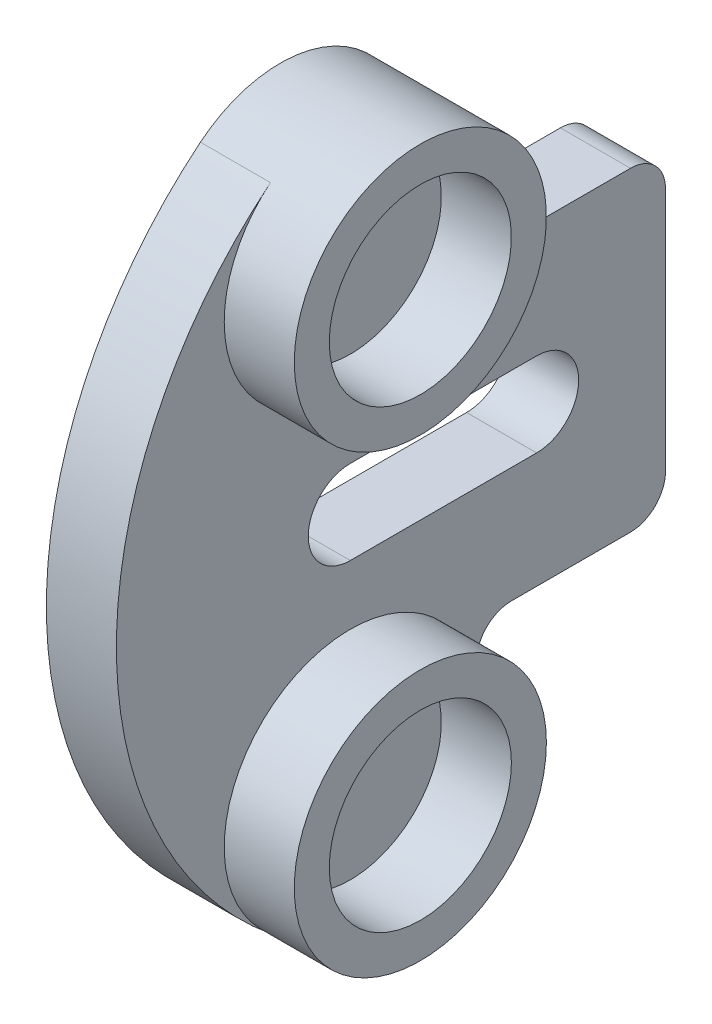
SolidWorks part; units mm, degrees
ref_plane "Front Plane" through (0, 0, 0) normal (1, 0, 0) x (0, 1, 0)
ref_plane "Top Plane" through (0, 0, 0) normal (0, 0, 1) x (0, 1, 0)
ref_plane "Right Plane" through (0, 0, 0) normal (0, 1, 0) x (-1, 0, 0)
sketch "Sketch2" plane through (0, 0, 0) normal (1, 0, 0) x (0, 1, 0)
  line L0 (6, 26.6036) -> (6, 0)
  line L1 (32.5, 8.6036) -> (27.5, 8.6036)
  line L2 (22.5, 3.6036) -> (22.5, -13.3964)
  line L3 (17.5, -18.3964) -> (-17.5, -18.3964)
  line L4 (-22.5, -13.3964) -> (-22.5, 3.6036)
  line L5 (-27.5, 8.6036) -> (-32.5, 8.6036)
  line L6 (-6, 26.6036) -> (-6, 0)
  arc A0 (-46.4286, 38.0051) -> (46.4286, 38.0051) centre (0, 0) cw
  arc A1 (32.5, 8.6036) -> (46.4286, 38.0051) centre (32.5, 26.6036) ccw
  arc A2 (-32.5, 8.6036) -> (-46.4286, 38.0051) centre (-32.5, 26.6036) cw
  arc A4 (6, 26.6036) -> (-6, 26.6036) centre (0, 26.6036) ccw
  arc A5 (-17.5, -18.3964) -> (-22.5, -13.3964) centre (-17.5, -13.3964) cw
  arc A6 (22.5, -13.3964) -> (17.5, -18.3964) centre (17.5, -13.3964) cw
  arc A7 (27.5, 8.6036) -> (22.5, 3.6036) centre (27.5, 3.6036) ccw
  arc A8 (-22.5, 3.6036) -> (-27.5, 8.6036) centre (-27.5, 3.6036) ccw
  arc A9 (-6, 0) -> (6, 0) centre (0, 0) ccw
  point P6 (-43.3602, 41.4686)
  point P16 (0, -18.3964)
  point P19 (-22.5, -18.3964)
  point P22 (22.5, -18.3964)
  dimension "D1" = 60
  dimension "D2" = 36
  dimension "D4" = 45
  dimension "D6" = 5
  dimension "D7" = 36
  dimension "D8" = 12
  dimension "D9" = 12
  dimension "D3" = 65
  dimension "D5" = 45
extrude "Boss-Extrude1" add sketch "Sketch2" along normal blind 10
sketch "Sketch3" plane through (0, 0, 0) normal (1, 0, 0) x (0, 1, 0)
  line L0 (0, 0) -> (0, 62.8579) construction
  line L1 (-17.5, -18.3964) -> (17.5, -18.3964) construction
  circle A0 centre (-32.5, 26.6036) radius 18
  circle A1 centre (-32.5, 26.6036) radius 13
  circle A2 centre (32.5, 26.6036) radius 13
  circle A3 centre (32.5, 26.6036) radius 18
  dimension "D2" = 36
  dimension "D3" = 26
  dimension "D1" = 45
extrude "Boss-Extrude2" add sketch "Sketch3" along normal blind 20
